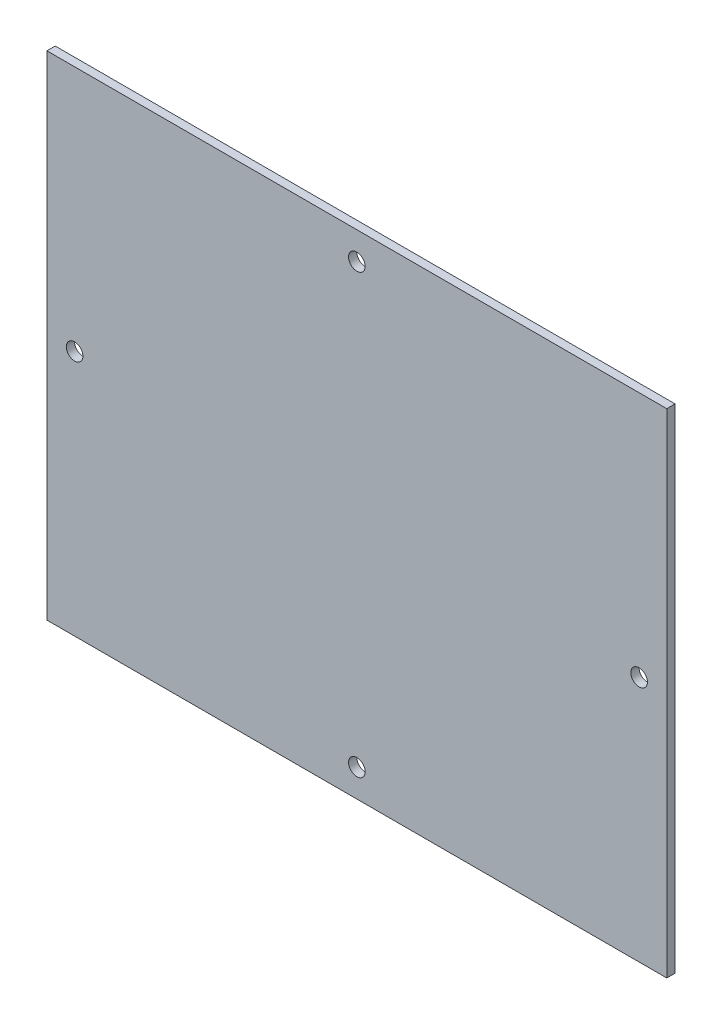
SolidWorks part; units mm, degrees
ref_plane "前视基准面" through (0, 0, 0) normal (0, 0, 1) x (1, 0, 0)
ref_plane "上视基准面" through (0, 0, 0) normal (0, 1, 0) x (1, 0, 0)
ref_plane "右视基准面" through (0, 0, 0) normal (1, 0, 0) x (0, 0, -1)
sketch "草图1" plane through (0, 0, 0) normal (0, 0, 1) x (1, 0, 0)
  line L0 (61.1303, 59.697) -> (128.437, 59.697) construction
  line L1 (-60.2101, 0) -> (-60.2101, 32.426) construction
  line L2 (-116.2101, 15.152) -> (-116.2101, 104.242)
  line L3 (-116.2101, 104.242) -> (-4.2101, 104.242)
  line L4 (-4.2101, 15.152) -> (-4.2101, 104.242)
  line L5 (-116.2101, 15.152) -> (-4.2101, 15.152)
  circle A0 centre (-60.2101, 99.242) radius 1.5
  circle A1 centre (-111.2101, 59.697) radius 1.5
  circle A2 centre (-60.2101, 20.152) radius 1.5
  circle A3 centre (-9.2101, 59.697) radius 1.5
  point P19 (-60.2101, 104.242)
  point P20 (-4.2101, 59.697)
  point P21 (-116.2101, 59.697)
  dimension "D1" = 39.545
  dimension "D5" = 3
  dimension "D6" = 3
  dimension "D2" = 51
  dimension "D3" = 56
  dimension "D4" = 44.545
extrude "凸台-拉伸1" add sketch "草图1" along normal blind 1.5
equation "\"1。5\"=5"
